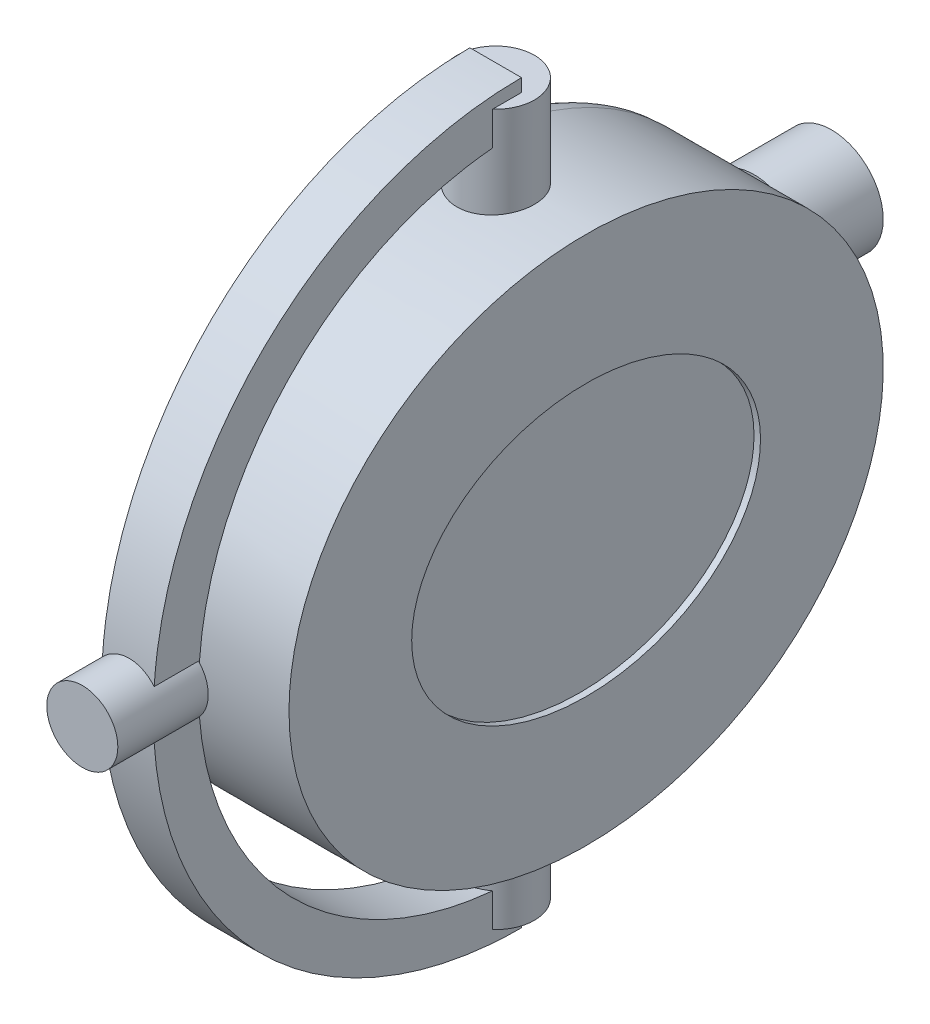
SolidWorks part; units mm, degrees
ref_plane "Front Plane" through (0, 0, 0) normal (1, 0, 0) x (0, 1, 0)
ref_plane "Top Plane" through (0, 0, 0) normal (0, 0, 1) x (0, 1, 0)
ref_plane "Right Plane" through (0, 0, 0) normal (0, 1, 0) x (-1, 0, 0)
sketch "Sketch1" plane through (0, 0, 0) normal (1, 0, 0) x (0, 1, 0)
  ellipse E0 centre (0, -56) end of major axis (0, -102) minor radius 41
extrude "Housing" add sketch "Sketch1" along normal mid plane 28
fillet "HousingFillet" radius 6 1 edges at (-14, 0, -10)
sketch "Sketch2" plane through (0, 0, 0) normal (1, 0, 0) x (0, 1, 0)
  line L0 (-57, -56) -> (-50, -56)
  line L1 (50, -56) -> (57, -56)
  spline S0 degree 3 poles (57, -56) (57.0008, -52.0206) (56.3722, -46.0519) (54.3094, -38.3538) (52.1674, -32.7736) (49.4538, -27.4479) (46.1983, -22.4349) (42.4367, -17.7898) (38.2102, -13.5633) (33.5651, -9.8017) (28.5521, -6.5462) (23.2264, -3.8326) (17.6462, -1.6906) (11.8726, -0.1436) (5.969, 0.7915) (0, 1.1043) (-5.969, 0.7915) (-11.8726, -0.1436) (-17.6462, -1.6906) (-23.2264, -3.8326) (-28.5521, -6.5462) (-33.5651, -9.8017) (-38.2102, -13.5633) (-42.4367, -17.7898) (-46.1983, -22.4349) (-49.4538, -27.4479) (-52.1674, -32.7736) (-54.3094, -38.3538) (-56.3722, -46.0519) (-57.0008, -52.0206) (-57, -56) knots 0 0 0 0 0.066667 0.1 0.133333 0.166667 0.2 0.233333 0.266667 0.3 0.333333 0.366667 0.4 0.433333 0.466667 0.5 0.533333 0.566667 0.6 0.633333 0.666667 0.7 0.733333 0.766667 0.8 0.833333 0.866667 0.9 0.933333 1 1 1 1
  spline S1 degree 3 poles (-50, -56) (-50.0007, -52.5093) (-49.4493, -47.2736) (-47.6398, -40.5209) (-45.7608, -35.626) (-43.3805, -30.9543) (-40.5248, -26.557) (-37.2252, -22.4823) (-33.5177, -18.7748) (-29.443, -15.4752) (-25.0457, -12.6195) (-20.374, -10.2392) (-15.4791, -8.3602) (-10.4146, -7.0032) (-5.236, -6.1829) (0, -5.9085) (5.236, -6.1829) (10.4146, -7.0032) (15.4791, -8.3602) (20.374, -10.2392) (25.0457, -12.6195) (29.443, -15.4752) (33.5177, -18.7748) (37.2252, -22.4823) (40.5248, -26.557) (43.3805, -30.9543) (45.7608, -35.626) (47.6398, -40.5209) (49.4493, -47.2736) (50.0007, -52.5093) (50, -56) knots 0 0 0 0 0.066667 0.1 0.133333 0.166667 0.2 0.233333 0.266667 0.3 0.333333 0.366667 0.4 0.433333 0.466667 0.5 0.533333 0.566667 0.6 0.633333 0.666667 0.7 0.733333 0.766667 0.8 0.833333 0.866667 0.9 0.933333 1 1 1 1
extrude "Yoke" add sketch "Sketch2" along normal mid plane 8
sketch "Sketch3" plane through (0, 0, 0) normal (0, 1, 0) x (-1, 0, 0)
  circle A0 centre (0, -56) radius 6
extrude "Hubs" add sketch "Sketch3" along normal mid plane 110
ref_plane "Plane_z_+1p0" through (0, 0, 1) normal (0, 0, 1) x (0, 1, 0)
sketch "Sketch4" plane through (0, 0, 1) normal (0, 0, 1) x (0, 1, 0)
  circle A0 centre (0, 0) radius 5.5
extrude "Stem" add sketch "Sketch4" along normal mid plane 14
ref_plane "Plane_x_-14p6" through (-14.6, 0, 0) normal (1, 0, 0) x (0, 1, 0)
sketch "Sketch5" plane through (-14.6, 0, 0) normal (1, 0, 0) x (0, 1, 0)
  circle A0 centre (0, -56) radius 31
  circle A1 centre (0, -56) radius 27
extrude "CapRing" add sketch "Sketch5" along normal mid plane 1.2
ref_plane "Plane_x_-14p3" through (-14.3, 0, 0) normal (1, 0, 0) x (0, 1, 0)
sketch "Sketch6" plane through (-14.3, 0, 0) normal (1, 0, 0) x (0, 1, 0)
  circle A0 centre (0, -56) radius 27
extrude "CapDisc" add sketch "Sketch6" along normal mid plane 0.6
ref_plane "Plane_x_+14p0" through (14, 0, 0) normal (1, 0, 0) x (0, 1, 0)
sketch "Sketch7" plane through (14, 0, 0) normal (1, 0, 0) x (0, 1, 0)
  ellipse E0 centre (0, -56) end of major axis (0, -83) minor radius 21
extrude "Grille" cut sketch "Sketch7" against normal mid plane 2
ref_plane "Plane_z_-102p0" through (0, 0, -102) normal (0, 0, 1) x (0, 1, 0)
sketch "Sketch8" plane through (0, 0, -102) normal (0, 0, 1) x (0, 1, 0)
  circle A0 centre (14, 0) radius 8
extrude "JackBoss" add sketch "Sketch8" along normal mid plane 12
ref_plane "Plane_z_-90p0" through (0, 0, -90) normal (0, 0, 1) x (0, 1, 0)
sketch "Sketch9" plane through (0, 0, -90) normal (0, 0, 1) x (0, 1, 0)
  circle A0 centre (14, 0) radius 3.4
extrude "JackHole" cut sketch "Sketch9" against normal mid plane 36
sketch "Sketch10" plane through (0, 0, -90) normal (0, 0, 1) x (0, 1, 0)
  circle A0 centre (14, 0) radius 5.5
extrude "JackClearance" [suppressed] cut sketch "Sketch10" against normal mid plane 36.5
